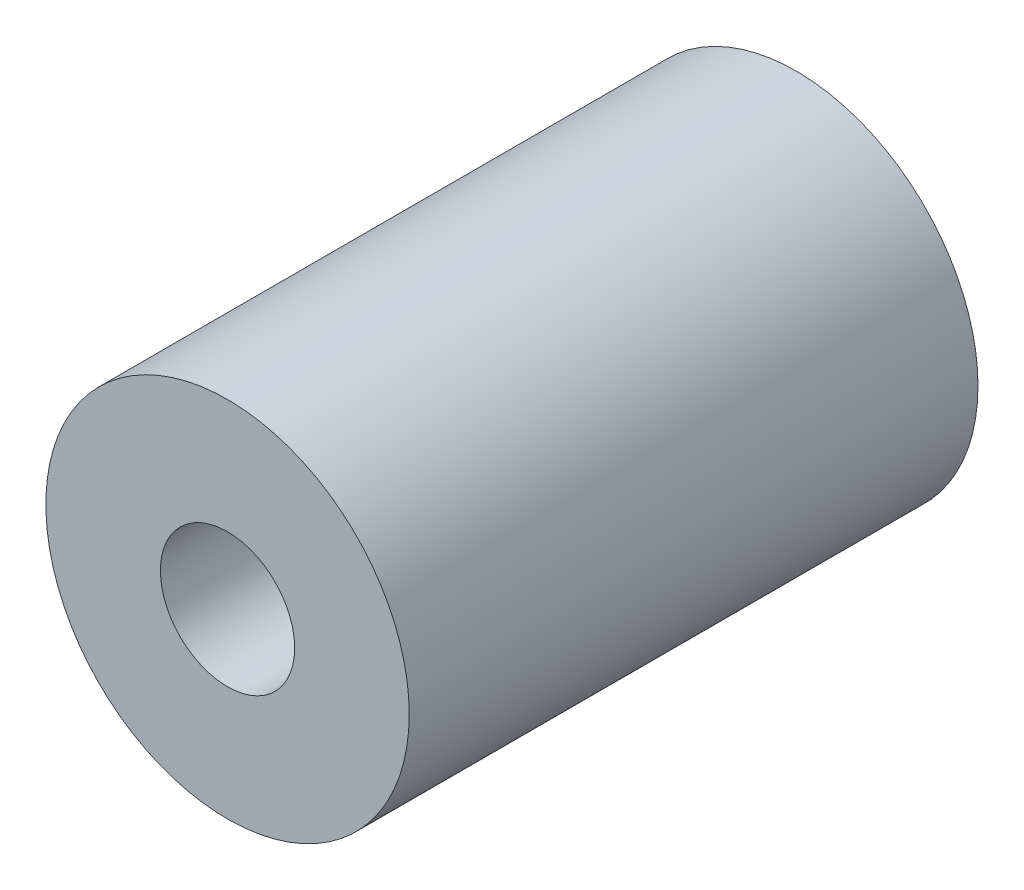
SolidWorks part; units mm, degrees
ref_plane "Ön Düzlem" through (0, 0, 0) normal (0, 0, 1) x (1, 0, 0)
ref_plane "Üst Düzlem" through (0, 0, 0) normal (0, 1, 0) x (1, 0, 0)
ref_plane "Sağ Düzlem" through (0, 0, 0) normal (1, 0, 0) x (0, 0, -1)
sketch "Sketch1" plane through (0, 0, 0) normal (0, 0, 1) x (1, 0, 0)
  circle A0 centre (0, 0) radius 2.3
  dimension "D1" = 4.6
extrude "Boss-Extrude1" add sketch "Sketch1" along normal blind 7.2
sketch "Sketch2" plane through (0, 0, 7.2) normal (0, 0, 1) x (1, 0, 0)
  circle A0 centre (0, 0) radius 0.85
  dimension "D1" = 1.7
extrude "Cut-Extrude1" cut sketch "Sketch2" against normal blind 3.6
